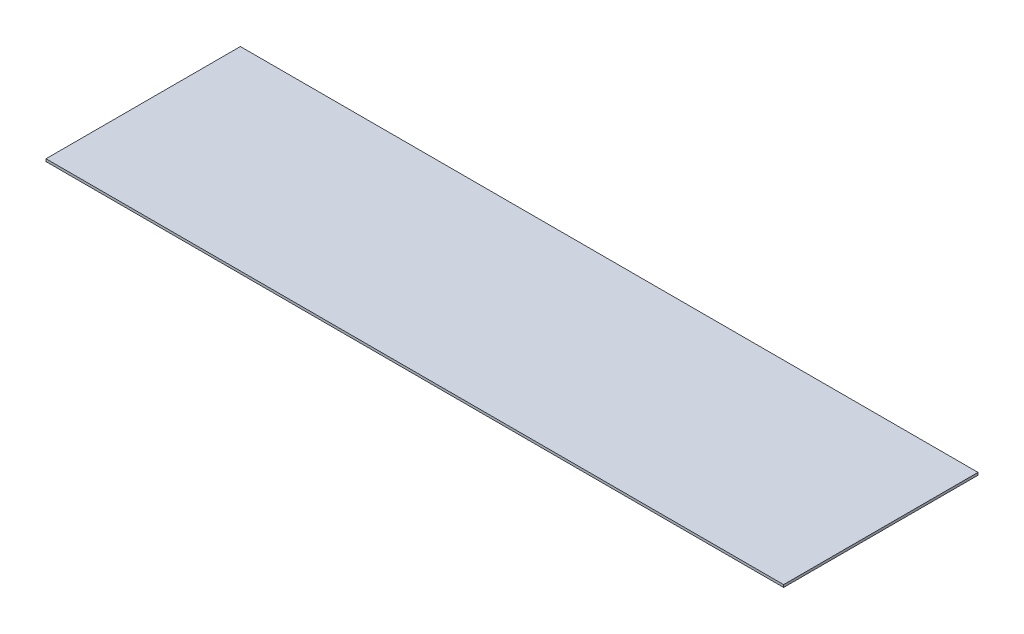
SolidWorks part; units mm, degrees
ref_plane "Front Plane" through (0, 0, 0) normal (0, 0, 1) x (1, 0, 0)
ref_plane "Top Plane" through (0, 0, 0) normal (0, 1, 0) x (1, 0, 0)
ref_plane "Right Plane" through (0, 0, 0) normal (1, 0, 0) x (0, 0, -1)
sketch "Sketch1" plane through (0, 0, 0) normal (0, 1, 0) x (1, 0, 0)
  line L1 (-65.2189, 30.8547) -> (404.6811, 30.8547)
  line L2 (-65.2189, 30.8547) -> (-65.2189, -92.9703)
  line L3 (-65.2189, -92.9703) -> (404.6811, -92.9703)
  line L4 (404.6811, 30.8547) -> (404.6811, -92.9703)
  dimension "D1" = 469.9
  dimension "D2" = 123.825
extrude "Boss-Extrude1" add sketch "Sketch1" against normal blind 1.5875
